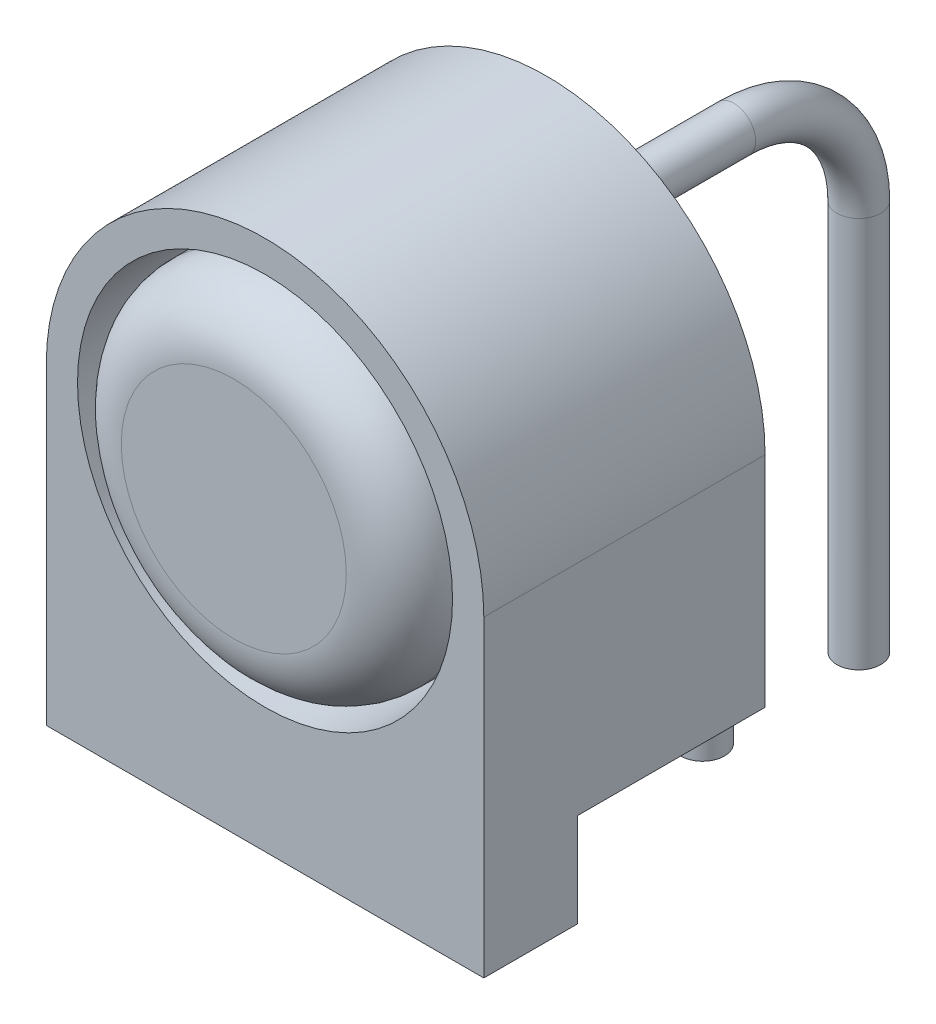
SolidWorks part; units mm, degrees
ref_plane "Спереди" through (0, 0, 0) normal (0, 0, 1) x (1, 0, 0)
ref_plane "Сверху" through (0, 0, 0) normal (0, 1, 0) x (1, 0, 0)
ref_plane "Справа" through (0, 0, 0) normal (1, 0, 0) x (0, 0, -1)
sketch "Эскиз1" plane through (0, 0, 0) normal (0, 0, 1) x (1, 0, 0)
  line L0 (0, 0) -> (0, -5) construction
  line L3 (-3.5, -3.5) -> (-3.5, 0)
  line L4 (3.5, -3.5) -> (3.5, 0)
  line L5 (3.5, -3.5) -> (3.5, -5)
  line L6 (-3.5, -3.5) -> (-3.5, -5)
  line L7 (-3.5, -5) -> (3.5, -5)
  arc A1 (3.5, 0) -> (-3.5, 0) centre (0, 0) ccw
extrude "Бобышка-Вытянуть2" add sketch "Эскиз1" along normal blind 4.5
sketch "Эскиз2" plane through (0, 0, 4.5) normal (0, 0, 1) x (1, 0, 0)
  line L0 (0, -5) -> (0, 0) construction
  line L1 (-3.5, -5) -> (3.5, -5) construction
  circle A0 centre (0, 0) radius 3
extrude "Вырез-Вытянуть1" cut sketch "Эскиз2" against normal blind 3.5
sketch "Эскиз3" plane through (0, 0, 1) normal (0, 0, 1) x (1, 0, 0)
  circle A0 centre (0, 0) radius 2.8
extrude "Бобышка-Вытянуть3" add sketch "Эскиз3" along normal blind 4
sketch "Эскиз4" plane through (0, -5, 0) normal (0, -1, 0) x (1, 0, 0)
  line L0 (0.1462, 4.5) -> (0.1462, 3) construction
  line L1 (-3.5, 4.5) -> (3.5, 4.5) construction
  line L2 (0.1462, 3) -> (-3.5, 3)
  line L3 (-3.5, 4.5) -> (-3.5, 0) construction
  line L4 (-3.5, 3) -> (-3.5, 0)
  line L5 (-3.5, 0) -> (3.5, 0)
  line L6 (3.5, 0) -> (3.5, 3)
  line L7 (3.5, 4.5) -> (3.5, 0) construction
  line L8 (3.5, 3) -> (0.1462, 3)
extrude "Вырез-Вытянуть2" cut sketch "Эскиз4" against normal blind 1.5
ref_plane "Плоскость1" through (0, 0, 0) normal (-1, 0, 0) x (0, 0, 1)
sketch "Эскиз6" plane through (0, 0, 0) normal (-1, 0, 0) x (0, 0, 1)
  line L0 (-1.0904, 0) -> (-1.0904, 1.27) construction
  line L1 (-1.0904, 0) -> (-1.0904, -1.27) construction
  line L2 (0, -1.27) -> (-1.5, -1.27)
  line L3 (0, -3.5) -> (0, 0) construction
  line L4 (0, 1.27) -> (-3, 1.27)
  line L5 (0, 3.5) -> (0, 0) construction
  line L6 (3, -5) -> (-6.5162, -5) construction
  line L7 (-2.5, -2.27) -> (-2.5, -5)
  line L8 (-5, -0.73) -> (-5, -5)
  line L9 (-2.5, -5) -> (-2.5, -7)
  line L10 (-5, -5) -> (-5, -7)
  arc A0 (-1.5, -1.27) -> (-2.5, -2.27) centre (-1.5, -2.27) ccw
  arc A2 (-5, -0.73) -> (-3, 1.27) centre (-3, -0.73) cw
  point P8 (0, 0)
  dimension "D1" = 1
  dimension "D3" = 2
sweep "По траектории2" add path "Эскиз6" circular profile diameter 0.7 parameters "D3"=0.7
sketch "Эскиз107" plane through (0, 0, 0) normal (-1, 0, 0) x (0, 0, 1)
  line L0 (-0.2224, 0) -> (-0.2224, 1.27) construction
  line L1 (0, 1.27) -> (-3, 1.27)
  line L2 (0, 3.5) -> (0, 0) construction
  line L3 (-5, -0.73) -> (-5, -6.9847)
  arc A0 (-5, -0.73) -> (-3, 1.27) centre (-3, -0.73) cw
  dimension "D1" = 2
sweep "По траектории3" add path "Эскиз107" circular profile diameter 0.7 parameters "D3"=0.7
fillet "Скругление1" radius 1 1 edges at (2.8, 0, 5)
